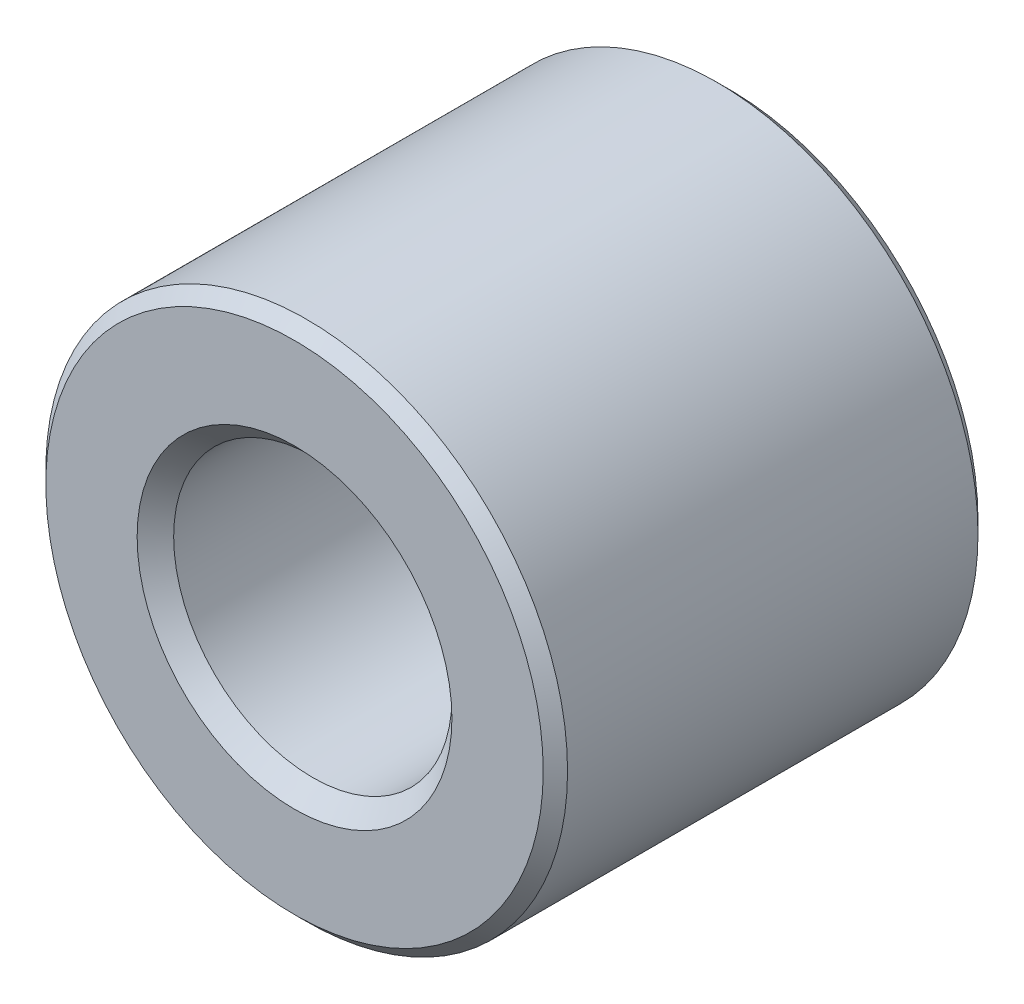
SolidWorks part; units mm, degrees
material "6061 Alloy"
ref_plane "Front Plane" through (0, 0, 0) normal (0, 0, 1) x (1, 0, 0)
ref_plane "Top Plane" through (0, 0, 0) normal (0, 1, 0) x (1, 0, 0)
ref_plane "Right Plane" through (0, 0, 0) normal (1, 0, 0) x (0, 0, -1)
sketch "Sketch1" plane through (0, 0, 0) normal (0, 0, 1) x (1, 0, 0)
  circle A0 centre (0, 0) radius 3 construction
  circle A1 centre (0, 0) radius 1.6 construction
  point P4 (0, 3)
  dimension "ID" = 3.2
  dimension "OD" = 6
sketch "Sketch2" plane through (0, 0, 0) normal (1, 0, 0) x (0, 0, -1)
  line L0 (-2.5, 3) -> (2.5, 3) construction
  dimension "Length" = 5
sketch "Sketch3" plane through (0, 0, 0) normal (0, 0, 1) x (1, 0, 0)
  circle A0 centre (0, 0) radius 1.6 construction
  circle A1 centre (0, 0) radius 3 construction
  circle A2 centre (0, 0) radius 1.6
  circle A3 centre (0, 0) radius 3
extrude "Boss-Extrude1" add sketch "Sketch3" against normal up to vertex (2.5 mm away) and the other way up to vertex (2.5 mm away) up to point (0, 3, -2.5) other way up to point (0, 3, 2.5)
chamfer "Chamfer1" distance 0.14 angle 45 2 edges at (3, 0, 2.5) (3, 0, -2.5)
chamfer "Chamfer2" distance 0.21 angle 45 2 edges at (1.6, 0, 2.5) (1.6, 0, -2.5)
equation "\"D1@Chamfer1\"=(\"OD@Sketch1\"-\"ID@Sketch1\")*0.05"
equation "\"D1@Chamfer2\"=(\"OD@Sketch1\"-\"ID@Sketch1\")*0.075"
